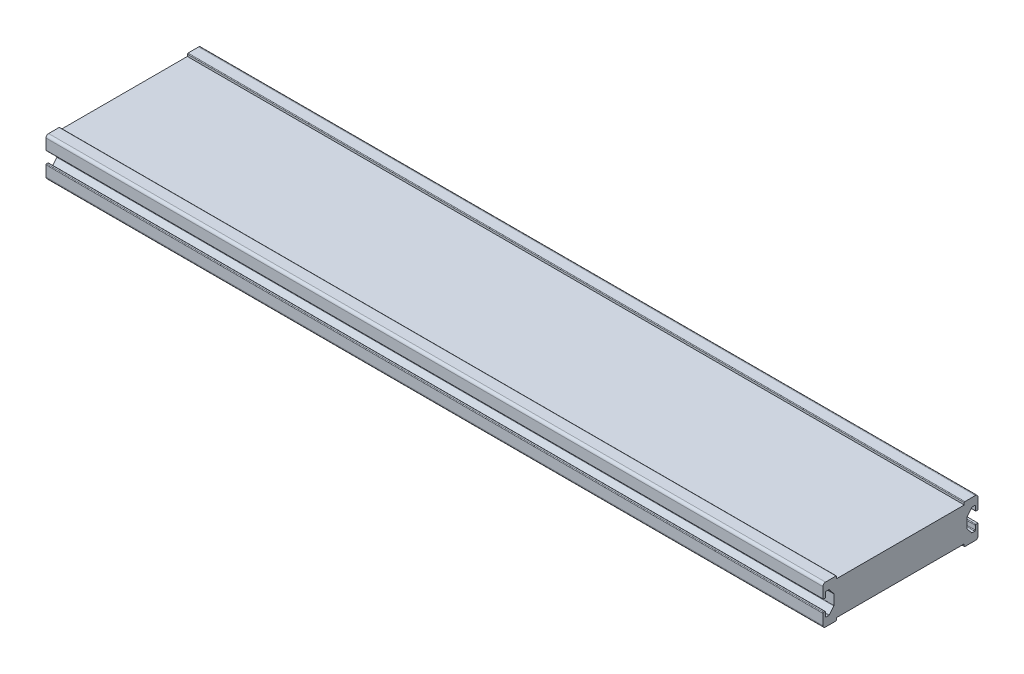
SolidWorks part; units mm, degrees
ref_plane "Front Plane" through (0, 0, 0) normal (0, 0, 1) x (1, 0, 0)
ref_plane "Top Plane" through (0, 0, 0) normal (0, 1, 0) x (1, 0, 0)
ref_plane "Right Plane" through (0, 0, 0) normal (1, 0, 0) x (0, 0, -1)
sketch "Sketch1" plane through (0, 0, 0) normal (0, 0, 1) x (1, 0, 0)
  line L1 (0, 0) -> (598.4875, 0)
  line L2 (0, 0) -> (0, 30)
  line L3 (0, 30) -> (598.4875, 30)
  line L4 (598.4875, 0) -> (598.4875, 30)
  dimension "D1" = 598.4875
  dimension "D2" = 30
extrude "Boss-Extrude1" add sketch "Sketch1" along normal blind 119.5 contours L3 L4 L1 L2
fillet "Fillet1" radius 2 4 edges at (299.2438, 0, 119.5) (299.2437, 30, 119.5) (299.2438, 0, 0) (299.2437, 30, 0)
sketch "Sketch2" plane through (598.4875, 0, 0) normal (1, 0, 0) x (0, 0, -1)
  line L0 (-119.5, 19.4) -> (-119.5, 10.6)
  line L1 (-119.5, 2) -> (-119.5, 28) construction
  line L3 (-119.5, 10.6) -> (-117.9781, 10.6)
  line L4 (-119.5, 19.4) -> (-117.9781, 19.4)
  line L5 (-117.5, 30) -> (-2, 30) construction
  line L6 (-117.4781, 19.9) -> (-117.4781, 23.13)
  line L7 (-117.4781, 10.1) -> (-117.4781, 6.87)
  line L8 (-110.9953, 11.175) -> (-110.9953, 18.825)
  line L9 (-116.9781, 6.37) -> (-114.9981, 6.37)
  line L10 (-114.6103, 6.5544) -> (-111.1075, 10.8594)
  line L11 (-111.1075, 19.1406) -> (-114.6103, 23.4456)
  line L13 (-116.9781, 23.63) -> (-114.9981, 23.63)
  arc A0 (-117.9781, 10.6) -> (-117.4781, 10.1) centre (-117.9781, 10.1) cw
  arc A1 (-117.9781, 19.4) -> (-117.4781, 19.9) centre (-117.9781, 19.9) ccw
  arc A2 (-117.4781, 23.13) -> (-116.9781, 23.63) centre (-116.9781, 23.13) cw
  arc A3 (-114.6103, 23.4456) -> (-114.9981, 23.63) centre (-114.9981, 23.13) ccw
  arc A4 (-110.9953, 18.825) -> (-111.1075, 19.1406) centre (-111.4953, 18.825) ccw
  arc A5 (-110.9953, 11.175) -> (-111.1075, 10.8594) centre (-111.4953, 11.175) cw
  arc A6 (-114.9981, 6.37) -> (-114.6103, 6.5544) centre (-114.9981, 6.87) ccw
  arc A7 (-117.4781, 6.87) -> (-116.9781, 6.37) centre (-116.9781, 6.87) ccw
  point P12 (0, 0)
  point P15 (-115.1655, 6.35)
  point P18 (-117.4781, 10.6)
  point P33 (-117.4781, 6.37)
  point P34 (-121.3357, 5.3743)
  point P35 (-119.5116, -10.4797)
  point P36 (-119.4561, -4.8434)
  point P37 (-111.4468, -20.854)
  dimension "D6" = 0.5
  dimension "D1" = 8.8
  dimension "D2" = 10.6
  dimension "D3" = 3.23
  dimension "D4" = 1.98
  dimension "D7" = 5.55
  dimension "D8" = 7.65
extrude "Cut-Extrude1" cut sketch "Sketch2" against normal up to next contours L3 A0 L7 A7 L9 A6 L10 A5 L8 A4 L11 A3 L13 A2 L6 A1 L4 L0
ref_plane "Plane1" through (0, 0, 59.75) normal (0, 0, -1) x (-1, 0, 0)
mirror "Mirror1" about plane through (0, 0, 59.75) normal (0, 0, -1) of "Cut-Extrude1"
fillet "Fillet2" radius 0.5 2 edges at (299.2438, 10.6, 119.5) (299.2437, 19.4, 119.5)
sketch "Sketch3" plane through (598.4875, 0, 0) normal (1, 0, 0) x (0, 0, -1)
  line L0 (-117.5, 30) -> (-2, 30) construction
  line L1 (-108.9, 30) -> (-10.6, 30)
  line L2 (-108.9, 30) -> (-108.9, 27.98)
  line L3 (-108.9, 27.98) -> (-10.6, 27.98)
  line L4 (-10.6, 30) -> (-10.6, 27.98)
  line L5 (-119.5, 19.9) -> (-119.5, 28) construction
  line L6 (0, 19.4) -> (0, 28) construction
  dimension "D1" = 10.6
  dimension "D2" = 10.6
  dimension "D3" = 2.02
extrude "Cut-Extrude2" cut sketch "Sketch3" against normal up to next contours L3 L4 L1 L2
ref_plane "Plane2" through (0, 15, 0) normal (0, 1, 0) x (1, 0, 0)
mirror "Mirror2" about plane through (0, 15, 0) normal (0, 1, 0) of "Cut-Extrude2"
fillet "Fillet3" radius 0.5 4 edges at (299.2437, 30, 10.6) (299.2437, 30, 108.9) (299.2437, 0, 108.9) (299.2437, 0, 10.6)
